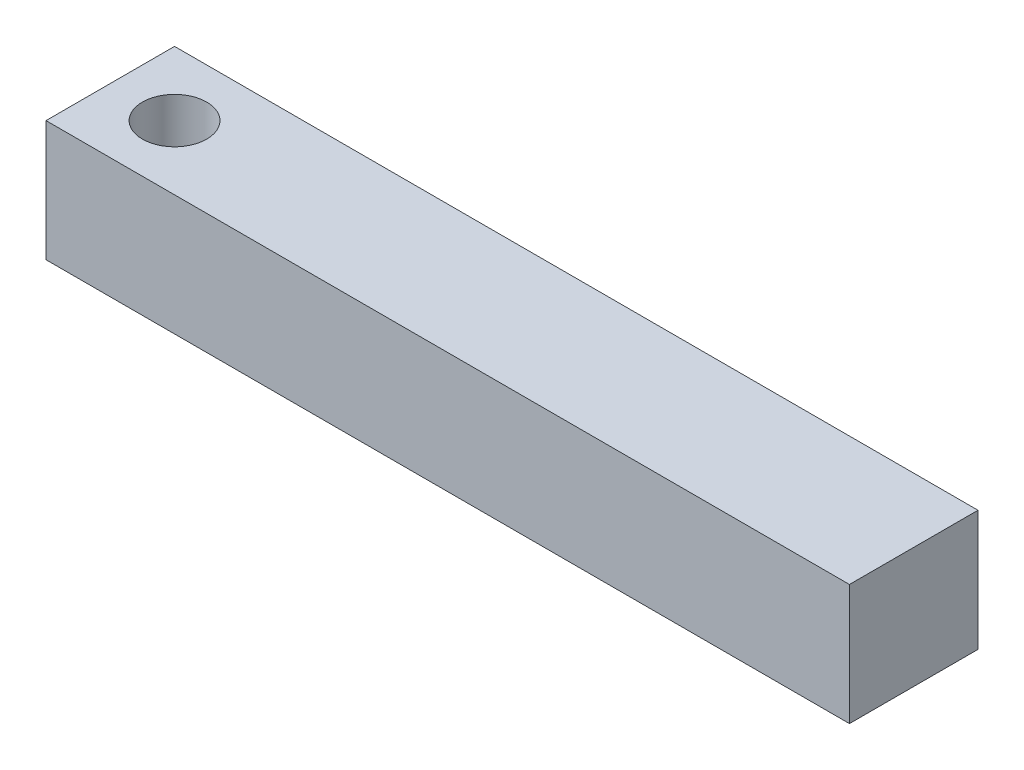
SolidWorks part; units mm, degrees
ref_plane "Plano frontal" through (0, 0, 0) normal (0, 0, 1) x (1, 0, 0)
ref_plane "Plano superior" through (0, 0, 0) normal (0, 1, 0) x (1, 0, 0)
ref_plane "Plano direito" through (0, 0, 0) normal (1, 0, 0) x (0, 0, -1)
sketch "Esboço1" plane through (0, 0, 0) normal (0, 1, 0) x (1, 0, 0)
  line L0 (-53.2002, 0) -> (55.646, 0) construction
  line L1 (-50, 8) -> (50, 8)
  line L2 (-50, 8) -> (-50, -8)
  line L3 (-50, -8) -> (50, -8)
  line L4 (50, 8) -> (50, -8)
  line L5 (-50, 8) -> (50, -8) construction
  line L6 (-50, -8) -> (50, 8) construction
  circle A0 centre (-42, 0) radius 4
  point P0 (0, 0)
  dimension "D3" = 8
  dimension "D4" = 8
  dimension "D5" = 8
  dimension "D1" = 16
  dimension "D2" = 100
extrude "Ressalto-extrusão1" add sketch "Esboço1" along normal blind 15
